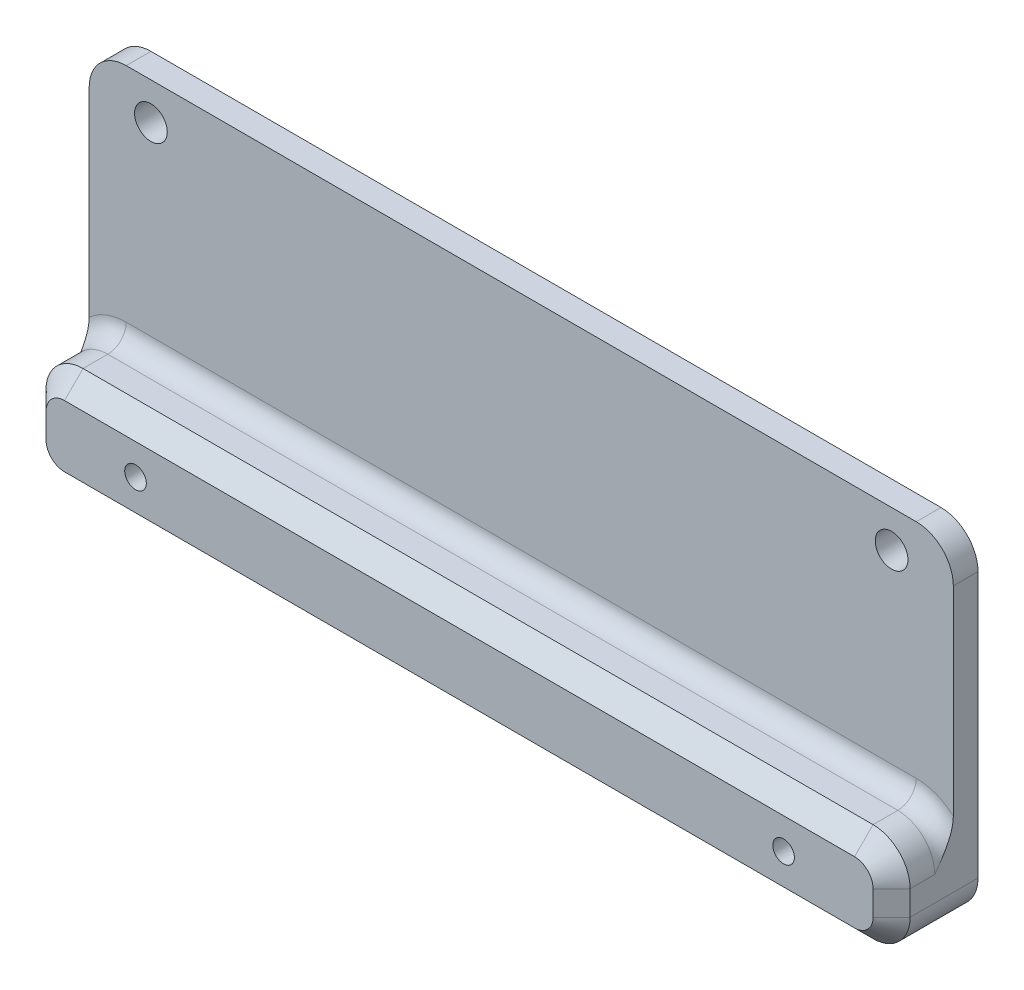
SolidWorks part; units mm, degrees
ref_plane "Front Plane" through (0, 0, 0) normal (0, 0, 1) x (1, 0, 0)
ref_plane "Top Plane" through (0, 0, 0) normal (0, 1, 0) x (1, 0, 0)
ref_plane "Right Plane" through (0, 0, 0) normal (1, 0, 0) x (0, 0, -1)
sketch "Sketch1" plane through (0, 0, 0) normal (0, 0, 1) x (1, 0, 0)
  line L0 (-70, 21.5) -> (70, 21.5) construction
  line L1 (-70, -27.5) -> (70, -27.5)
  line L2 (-70, -27.5) -> (-70, 27.5)
  line L3 (-70, 27.5) -> (70, 27.5)
  line L4 (70, -27.5) -> (70, 27.5)
  line L5 (0, 27.5) -> (0, -27.5) construction
  line L6 (-70, 0) -> (70, 0) construction
  line L7 (-70, -19.5) -> (70, -19.5) construction
  circle A0 centre (-60, 21.5) radius 2.65
  circle A1 centre (60, 21.5) radius 2.65
  circle A2 centre (-52.5, -19.5) radius 1.75 construction
  circle A3 centre (52.5, -19.5) radius 1.75 construction
  point P0 (0, 0)
  dimension "D1" = 120
  dimension "D2" = 5.3
  dimension "D4" = 10
  dimension "D7" = 3.5
  dimension "D8" = 105
  dimension "D3" = 6
  dimension "D5" = 8
  dimension "D6" = 41
extrude "Boss-Extrude1" add sketch "Sketch1" along normal blind 4
sketch "Sketch2" plane through (0, 0, 4) normal (0, 0, 1) x (1, 0, 0)
  line L1 (-70, -11.5) -> (70, -11.5)
  line L2 (-70, -11.5) -> (-70, -27.5)
  line L3 (-70, -27.5) -> (70, -27.5)
  line L4 (70, -11.5) -> (70, -27.5)
  line L5 (0, -27.5) -> (0, -11.5) construction
  line L6 (-70, -19.5) -> (70, -19.5) construction
  line L7 (-70, -19.5) -> (70, -19.5) construction
  line L8 (-70, -27.5) -> (-70, 27.5) construction
  point P0 (0, -19.5)
extrude "Boss-Extrude2" add sketch "Sketch2" along normal blind 10
sketch "Sketch3" plane through (0, 0, 0) normal (0, 0, -1) x (-1, 0, 0)
  line L0 (70, -19.5) -> (-70, -19.5) construction
  line L1 (-67, -14.5) -> (67, -14.5)
  line L2 (-67, -14.5) -> (-67, -24.5)
  line L3 (-67, -24.5) -> (67, -24.5)
  line L4 (67, -14.5) -> (67, -24.5)
  line L5 (0, -24.5) -> (0, -14.5) construction
  line L6 (-67, -19.5) -> (67, -19.5) construction
  line L7 (70, -27.5) -> (70, 27.5) construction
  line L8 (70, -27.5) -> (-70, -27.5) construction
  point P0 (0, -19.5)
  dimension "D1" = 3
  dimension "D2" = 3
extrude "Cut-Extrude1" cut sketch "Sketch3" against normal offset from surface (11 mm away) 3 up to face at (0, -19.5, 14)
sketch "Sketch4" plane through (0, 0, 11) normal (0, 0, -1) x (-1, 0, 0)
  circle A0 centre (52.5, -19.5) radius 1.75 construction
  circle A1 centre (-52.5, -19.5) radius 1.75 construction
  circle A2 centre (52.5, -19.5) radius 1.75
  circle A3 centre (-52.5, -19.5) radius 1.75
extrude "Cut-Extrude2" cut sketch "Sketch4" against normal through all from offset 0.3 offset against normal yes
fillet "Fillet1" radius 3 4 edges at (-67, -24.5, 5.5) (67, -24.5, 5.5) (67, -14.5, 5.5) (-67, -14.5, 5.5)
fillet "Fillet2" radius 6 6 edges at (-70, -27.5, 7) (-70, 27.5, 2) (70, 27.5, 2) (70, -11.5, 9) (70, -27.5, 7) (-70, -11.5, 9)
fillet "Fillet3" radius 3 3 edges at (68.2426, -13.2574, 4) (0, -11.5, 4) (-68.2426, -13.2574, 4)
chamfer "Chamfer1" distance 1 angle 45 8 edges at (-66.1213, -23.6213, 11) (0, -24.5, 11) (66.1213, -23.6213, 11) (67, -19.5, 11) (66.1213, -15.3787, 11) (0, -14.5, 11) (-66.1213, -15.3787, 11) (-67, -19.5, 11)
chamfer "Chamfer2" distance 3 angle 45 8 edges at (68.2426, -13.2574, 14) (0, -11.5, 14) (70, -19.5, 14) (-68.2426, -13.2574, 14) (68.2426, -25.7426, 14) (-70, -19.5, 14) (0, -27.5, 14) (-68.2426, -25.7426, 14)
